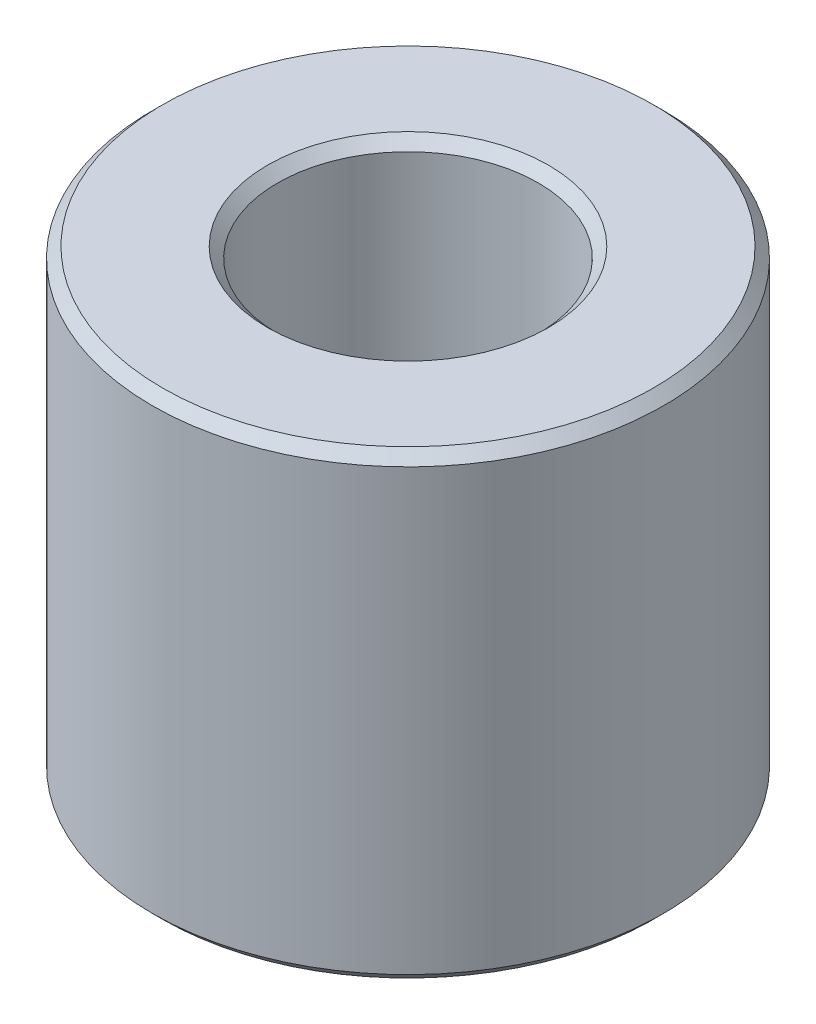
SolidWorks part; units mm, degrees
material "6061-T6 (SS)"
ref_plane "Front Plane" through (0, 0, 0) normal (0, 0, 1) x (1, 0, 0)
ref_plane "Top Plane" through (0, 0, 0) normal (0, 1, 0) x (1, 0, 0)
ref_plane "Right Plane" through (0, 0, 0) normal (1, 0, 0) x (0, 0, -1)
sketch "Sketch1" plane through (0, 0, 0) normal (1, 0, 0) x (0, 0, -1)
  line L0 (0, 2.1339) -> (0, -2.1339) construction
  line L1 (2.55, 4.3) -> (2.75, 4.5)
  line L2 (2.75, 4.5) -> (4.8, 4.5)
  line L3 (2.55, 4.3) -> (2.55, -4.3)
  line L4 (2.75, -4.5) -> (4.8, -4.5)
  line L5 (5, 4.3) -> (5, -4.3)
  line L6 (2.55, 4.5) -> (5, -4.5) construction
  line L7 (2.55, -4.5) -> (5, 4.5) construction
  line L8 (4.8, 4.5) -> (5, 4.3)
  line L9 (4.8, -4.5) -> (5, -4.3)
  line L10 (2.55, -4.3) -> (2.75, -4.5)
  point P0 (3.775, 0)
  point P4 (0, 0)
  dimension "D1" = 2.45
  dimension "D2" = 9
  dimension "D3" = 2.55
revolve "Revolve1" add sketch "Sketch1" angle 360 about L0
